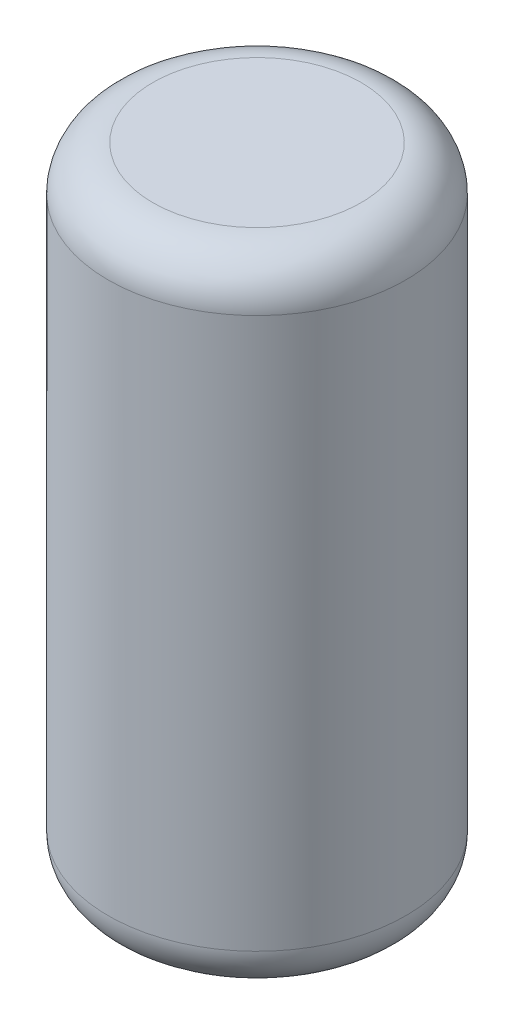
SolidWorks part; units mm, degrees
material "Полиуретановый жесткий пенопласт"
ref_plane "Спереди" through (0, 0, 0) normal (0, 0, 1) x (1, 0, 0)
ref_plane "Сверху" through (0, 0, 0) normal (0, 1, 0) x (1, 0, 0)
ref_plane "Справа" through (0, 0, 0) normal (1, 0, 0) x (0, 0, -1)
sketch "Эскиз1" plane through (0, 0, 0) normal (0, 0, 1) x (1, 0, 0)
  line L1 (0, 0) -> (50, 0)
  line L2 (0, 0) -> (0, 215)
  line L3 (0, 215) -> (50, 215)
  line L4 (50, 0) -> (50, 215)
  dimension "D1" = 50
  dimension "D2" = 215
revolve "Повернуть1" add sketch "Эскиз1" angle 360 about L2
fillet "Скругление1" radius 15 2 edges at (0, 0, -50) (0, 215, -50)
